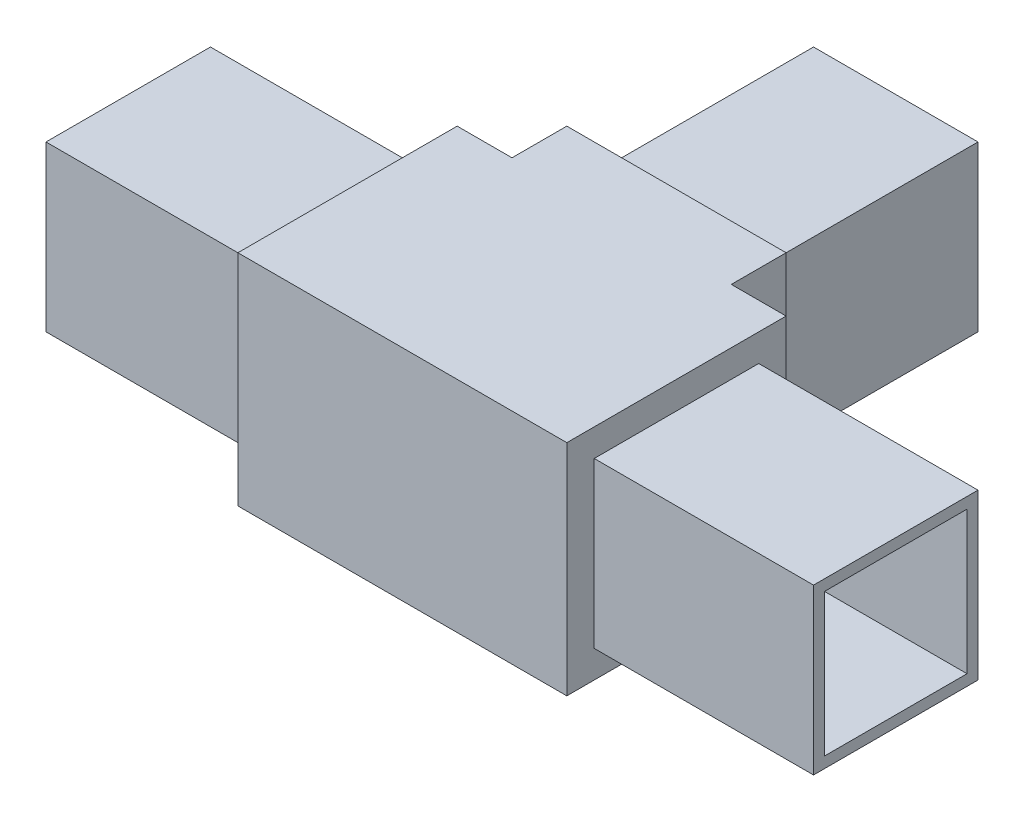
SolidWorks part; units mm, degrees
ref_plane "Alzado" through (0, 0, 0) normal (0, 0, 1) x (1, 0, 0)
ref_plane "Planta" through (0, 0, 0) normal (0, 1, 0) x (1, 0, 0)
ref_plane "Vista lateral" through (0, 0, 0) normal (1, 0, 0) x (0, 0, -1)
sketch "Croquis1" plane through (0, 0, 0) normal (0, 1, 0) x (1, 0, 0)
  line L1 (20, -20) -> (-20, -20)
  line L2 (20, -20) -> (20, 20)
  line L3 (20, 20) -> (-20, 20)
  line L4 (-20, -20) -> (-20, 20)
  line L5 (20, -20) -> (-20, 20) construction
  line L6 (20, 20) -> (-20, -20) construction
  line L7 (20, -20) -> (70, -20)
  line L8 (20, -20) -> (20, 20)
  line L9 (20, 20) -> (70, 20)
  line L10 (70, -20) -> (70, 20)
  line L11 (-20, 20) -> (20, 20)
  line L12 (-20, 20) -> (-20, 70)
  line L13 (-20, 70) -> (20, 70)
  line L14 (20, 20) -> (20, 70)
  line L15 (-20, -20) -> (-70, -20)
  line L16 (-20, -20) -> (-20, 20)
  line L17 (-20, 20) -> (-70, 20)
  line L18 (-70, -20) -> (-70, 20)
  point P0 (0, 0)
  dimension "D1" = 40
  dimension "D2" = 40
  dimension "D3" = 50
  dimension "D4" = 50
  dimension "D5" = 50
extrude "Extruir1" add sketch "Croquis1" along normal blind 40 contours L3 L14 L13 L12 | L4 L1 L2 L3 | L7 L10 L9 L2 | L18 L15 L4 L17
sketch "Croquis2" plane through (70, 0, 0) normal (1, 0, 0) x (0, 0, -1)
  line L4 (-20, 0) -> (20, 0)
  line L5 (20, 0) -> (20, 40)
  line L6 (20, 40) -> (-20, 40)
  line L7 (-20, 40) -> (-20, 0)
  line L8 (-20, 0) -> (20, 0)
  line L9 (20, 0) -> (20, 40)
  line L10 (20, 40) -> (-20, 40)
  line L11 (-20, 40) -> (-20, 0)
  line L16 (-15, 5) -> (15, 5)
  line L17 (15, 5) -> (15, 35)
  line L18 (15, 35) -> (-15, 35)
  line L19 (-15, 35) -> (-15, 5)
  line L20 (-15, 5) -> (15, 5)
  line L21 (15, 5) -> (15, 35)
  line L22 (15, 35) -> (-15, 35)
  line L23 (-15, 35) -> (-15, 5)
  dimension "D1" = 0
  dimension "D2" = 5
extrude "Extruir2" cut sketch "Croquis2" against normal blind 40
sketch "Croquis3" plane through (0, 0, -70) normal (0, 0, -1) x (-1, 0, 0)
  line L0 (-15, 5) -> (15, 5)
  line L1 (15, 5) -> (15, 35)
  line L2 (15, 35) -> (-15, 35)
  line L3 (-15, 35) -> (-15, 5)
  line L4 (-20, 0) -> (20, 0)
  line L5 (20, 0) -> (20, 40)
  line L6 (20, 40) -> (-20, 40)
  line L7 (-20, 40) -> (-20, 0)
  line L8 (-20, 0) -> (20, 0)
  line L9 (20, 0) -> (20, 40)
  line L10 (20, 40) -> (-20, 40)
  line L11 (-20, 40) -> (-20, 0)
  line L16 (20, 0) -> (20, 40) construction
  dimension "D1" = 0
  dimension "D2" = 5
extrude "Extruir3" cut sketch "Croquis3" against normal blind 40
sketch "Croquis5" plane through (-70, 0, 0) normal (-1, 0, 0) x (0, 0, 1)
  line L0 (-15, 5) -> (15, 5)
  line L1 (15, 5) -> (15, 35)
  line L2 (15, 35) -> (-15, 35)
  line L3 (-15, 35) -> (-15, 5)
  line L4 (-20, 0) -> (20, 0)
  line L5 (20, 0) -> (20, 40)
  line L6 (20, 40) -> (-20, 40)
  line L7 (-20, 40) -> (-20, 0)
  line L8 (-20, 0) -> (20, 0)
  line L9 (20, 0) -> (20, 40)
  line L10 (20, 40) -> (-20, 40)
  line L11 (-20, 40) -> (-20, 0)
  dimension "D1" = 0
  dimension "D2" = 5
extrude "Extruir4" cut sketch "Croquis5" against normal blind 40
shell "Vaciado1" thickness 2
